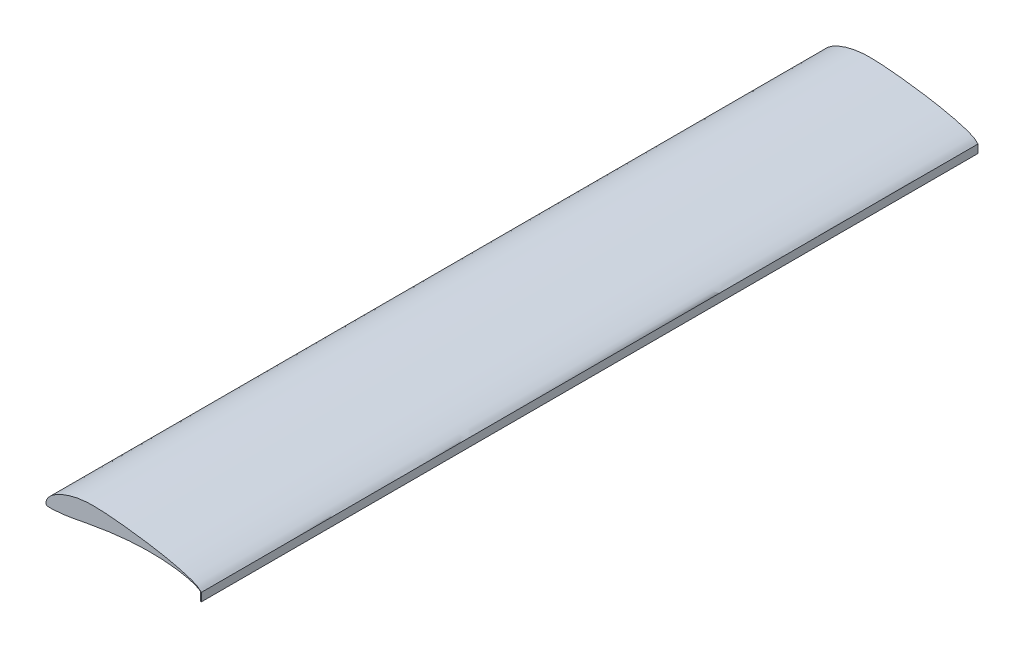
SolidWorks part; units mm, degrees
ref_plane "Front Plane" through (0, 0, 0) normal (0, 0, 1) x (1, 0, 0)
ref_plane "Top Plane" through (0, 0, 0) normal (0, 1, 0) x (1, 0, 0)
ref_plane "Right Plane" through (0, 0, 0) normal (1, 0, 0) x (0, 0, -1)
curve "Curve1"
  spline degree 3 poles (189.7628, 0.4947, 0) (190.6727, -0.123, 0) (189.8749, 0.4714, 0) (189.3453, 0.9911, 0) (188.1693, 2.0765, 0) (186.7819, 3.2312, 0) (184.8841, 4.3952, 0) (182.5241, 5.5233, 0) (179.675, 6.7006, 0) (176.3413, 7.9107, 0) (172.5383, 9.145, 0) (168.286, 10.3929, 0) (163.608, 11.6486, 0) (158.5302, 12.9003, 0) (153.0818, 14.1392, 0) (147.2951, 15.3574, 0) (141.2056, 16.5488, 0) (134.8488, 17.6986, 0) (128.2647, 18.8051, 0) (121.4914, 19.8543, 0) (114.5726, 20.848, 0) (107.5526, 21.7785, 0) (100.4822, 22.6427, 0) (93.4181, 23.4467, 0) (86.4187, 24.1704, 0) (79.541, 24.8, 0) (72.8334, 25.3003, 0) (66.3342, 25.6444, 0) (60.0796, 25.793, 0) (54.1015, 25.7772, 0) (48.4112, 25.4845, 0) (43.0065, 24.8913, 0) (37.8653, 24.0526, 0) (32.9864, 22.9661, 0) (28.3748, 21.6919, 0) (24.0501, 20.2528, 0) (20.0306, 18.6822, 0) (16.3413, 16.9888, 0) (12.994, 15.2068, 0) (10.0069, 13.3564, 0) (7.3989, 11.4629, 0) (5.1709, 9.5662, 0) (3.3552, 7.6458, 0) (1.9605, 5.7182, 0) (0.9303, 3.8429, 0) (0.2701, 2.0624, 0) (-0.0445, 0.419, 0) (0.0162, -0.9709, 0) (0.3741, -2.2457, 0) (1.7042, -2.8785, 0) (3.4926, -2.9673, 0) (5.9392, -3.0533, 0) (9.0159, -2.9207, 0) (12.688, -2.6769, 0) (16.9146, -2.2863, 0) (21.6525, -1.7579, 0) (26.8785, -1.0803, 0) (32.5902, -0.1332, 0) (38.8153, 1.0544, 0) (45.5849, 2.347, 0) (52.8659, 3.7117, 0) (60.6127, 5.092, 0) (68.7684, 6.436, 0) (77.2695, 7.6989, 0) (86.043, 8.8343, 0) (95.0099, 9.8092, 0) (104.0854, 10.5799, 0) (113.1786, 11.1261, 0) (122.1944, 11.4265, 0) (131.035, 11.4644, 0) (139.6018, 11.2374, 0) (147.7967, 10.7507, 0) (155.5211, 10.0106, 0) (162.6831, 9.0456, 0) (169.1894, 7.8836, 0) (174.9638, 6.5636, 0) (179.8998, 5.1511, 0) (183.9394, 3.6435, 0) (186.8216, 2.264, 0) (188.9465, 0.9883, 0) (189.7628, 0.4947, 0) (190.6727, -0.123, 0) (189.8749, 0.4714, 0) knots -0.009748 -0.004147 -0.001 0 0.00098 0.003649 0.007483 0.012095 0.017526 0.024052 0.031783 0.040678 0.05071 0.061833 0.073989 0.087118 0.101145 0.115991 0.13157 0.147788 0.164551 0.181758 0.199312 0.217095 0.23499 0.252857 0.270541 0.287887 0.304773 0.321101 0.336806 0.3518 0.366031 0.379616 0.392653 0.40517 0.417172 0.428604 0.439419 0.449597 0.459102 0.467908 0.475988 0.483309 0.489875 0.495803 0.501149 0.505903 0.510047 0.513579 0.516447 0.51935 0.523823 0.529974 0.537716 0.546968 0.557637 0.56962 0.582804 0.597247 0.613135 0.630444 0.649056 0.668822 0.689595 0.71119 0.733427 0.756094 0.778989 0.80189 0.824567 0.846792 0.868338 0.888978 0.908492 0.926659 0.943286 0.958169 0.971136 0.981956 0.990252 0.995853 0.999 1 1.00098 1.003649 1.007483 periodic
sketch "Sketch1" plane through (0, 0, 0) normal (0, 0, 1) x (1, 0, 0)
  spline S0 degree 3 poles (189.7628, 0.4947) (190.6727, -0.123) (189.8749, 0.4714) (189.3453, 0.9911) (188.1693, 2.0765) (186.7819, 3.2312) (184.8841, 4.3952) (182.5241, 5.5233) (179.675, 6.7006) (176.3413, 7.9107) (172.5383, 9.145) (168.286, 10.3929) (163.608, 11.6486) (158.5302, 12.9003) (153.0818, 14.1392) (147.2951, 15.3574) (141.2056, 16.5488) (134.8488, 17.6986) (128.2647, 18.8051) (121.4914, 19.8543) (114.5726, 20.848) (107.5526, 21.7785) (100.4822, 22.6427) (93.4181, 23.4467) (86.4187, 24.1704) (79.541, 24.8) (72.8334, 25.3003) (66.3342, 25.6444) (60.0796, 25.793) (54.1015, 25.7772) (48.4112, 25.4845) (43.0065, 24.8913) (37.8653, 24.0526) (32.9864, 22.9661) (28.3748, 21.6919) (24.0501, 20.2528) (20.0306, 18.6822) (16.3413, 16.9888) (12.994, 15.2068) (10.0069, 13.3564) (7.3989, 11.4629) (5.1709, 9.5662) (3.3552, 7.6458) (1.9605, 5.7182) (0.9303, 3.8429) (0.2701, 2.0624) (-0.0445, 0.419) (0.0162, -0.9709) (0.3741, -2.2457) (1.7042, -2.8785) (3.4926, -2.9673) (5.9392, -3.0533) (9.0159, -2.9207) (12.688, -2.6769) (16.9146, -2.2863) (21.6525, -1.7579) (26.8785, -1.0803) (32.5902, -0.1332) (38.8153, 1.0544) (45.5849, 2.347) (52.8659, 3.7117) (60.6127, 5.092) (68.7684, 6.436) (77.2695, 7.6989) (86.043, 8.8343) (95.0099, 9.8092) (104.0854, 10.5799) (113.1786, 11.1261) (122.1944, 11.4265) (131.035, 11.4644) (139.6018, 11.2374) (147.7967, 10.7507) (155.5211, 10.0106) (162.6831, 9.0456) (169.1894, 7.8836) (174.9638, 6.5636) (179.8998, 5.1511) (183.9394, 3.6435) (186.8216, 2.264) (188.9465, 0.9883) (189.7628, 0.4947) (190.6727, -0.123) (189.8749, 0.4714) knots -0.009748 -0.004147 -0.001 0 0.00098 0.003649 0.007483 0.012095 0.017526 0.024052 0.031783 0.040678 0.05071 0.061833 0.073989 0.087118 0.101145 0.115991 0.13157 0.147788 0.164551 0.181758 0.199312 0.217095 0.23499 0.252857 0.270541 0.287887 0.304773 0.321101 0.336806 0.3518 0.366031 0.379616 0.392653 0.40517 0.417172 0.428604 0.439419 0.449597 0.459102 0.467908 0.475988 0.483309 0.489875 0.495803 0.501149 0.505903 0.510047 0.513579 0.516447 0.51935 0.523823 0.529974 0.537716 0.546968 0.557637 0.56962 0.582804 0.597247 0.613135 0.630444 0.649056 0.668822 0.689595 0.71119 0.733427 0.756094 0.778989 0.80189 0.824567 0.846792 0.868338 0.888978 0.908492 0.926659 0.943286 0.958169 0.971136 0.981956 0.990252 0.995853 0.999 1 1.00098 1.003649 1.007483 only from (190.5, 0) to (190.5, 0) construction
  spline S1 degree 3 poles (189.7628, 0.4947) (190.6727, -0.123) (189.8749, 0.4714) (189.3453, 0.9911) (188.1693, 2.0765) (186.7819, 3.2312) (184.8841, 4.3952) (182.5241, 5.5233) (179.675, 6.7006) (176.3413, 7.9107) (172.5383, 9.145) (168.286, 10.3929) (163.608, 11.6486) (158.5302, 12.9003) (153.0818, 14.1392) (147.2951, 15.3574) (141.2056, 16.5488) (134.8488, 17.6986) (128.2647, 18.8051) (121.4914, 19.8543) (114.5726, 20.848) (107.5526, 21.7785) (100.4822, 22.6427) (93.4181, 23.4467) (86.4187, 24.1704) (79.541, 24.8) (72.8334, 25.3003) (66.3342, 25.6444) (60.0796, 25.793) (54.1015, 25.7772) (48.4112, 25.4845) (43.0065, 24.8913) (37.8653, 24.0526) (32.9864, 22.9661) (28.3748, 21.6919) (24.0501, 20.2528) (20.0306, 18.6822) (16.3413, 16.9888) (12.994, 15.2068) (10.0069, 13.3564) (7.3989, 11.4629) (5.1709, 9.5662) (3.3552, 7.6458) (1.9605, 5.7182) (0.9303, 3.8429) (0.2701, 2.0624) (-0.0445, 0.419) (0.0162, -0.9709) (0.3741, -2.2457) (1.7042, -2.8785) (3.4926, -2.9673) (5.9392, -3.0533) (9.0159, -2.9207) (12.688, -2.6769) (16.9146, -2.2863) (21.6525, -1.7579) (26.8785, -1.0803) (32.5902, -0.1332) (38.8153, 1.0544) (45.5849, 2.347) (52.8659, 3.7117) (60.6127, 5.092) (68.7684, 6.436) (77.2695, 7.6989) (86.043, 8.8343) (95.0099, 9.8092) (104.0854, 10.5799) (113.1786, 11.1261) (122.1944, 11.4265) (131.035, 11.4644) (139.6018, 11.2374) (147.7967, 10.7507) (155.5211, 10.0106) (162.6831, 9.0456) (169.1894, 7.8836) (174.9638, 6.5636) (179.8998, 5.1511) (183.9394, 3.6435) (186.8216, 2.264) (188.9465, 0.9883) (189.7628, 0.4947) (190.6727, -0.123) (189.8749, 0.4714) knots -0.009748 -0.004147 -0.001 0 0.00098 0.003649 0.007483 0.012095 0.017526 0.024052 0.031783 0.040678 0.05071 0.061833 0.073989 0.087118 0.101145 0.115991 0.13157 0.147788 0.164551 0.181758 0.199312 0.217095 0.23499 0.252857 0.270541 0.287887 0.304773 0.321101 0.336806 0.3518 0.366031 0.379616 0.392653 0.40517 0.417172 0.428604 0.439419 0.449597 0.459102 0.467908 0.475988 0.483309 0.489875 0.495803 0.501149 0.505903 0.510047 0.513579 0.516447 0.51935 0.523823 0.529974 0.537716 0.546968 0.557637 0.56962 0.582804 0.597247 0.613135 0.630444 0.649056 0.668822 0.689595 0.71119 0.733427 0.756094 0.778989 0.80189 0.824567 0.846792 0.868338 0.888978 0.908492 0.926659 0.943286 0.958169 0.971136 0.981956 0.990252 0.995853 0.999 1 1.00098 1.003649 1.007483 only from (190.5, 0) to (190.5, 0)
extrude "Boss-Extrude1" add sketch "Sketch1" along normal blind 952.5
sketch "Sketch2" plane through (0, 0, 0) normal (0, 0, -1) x (-1, 0, 0)
  line L0 (0, 0) -> (-190.5, 0) construction
  line L1 (-190.5, 0) -> (-190.5, -25.3291) construction
  line L2 (0, 0) -> (0, -25.3291) construction
  spline S0 degree 3 poles (-189.8749, 0.4714) (-190.6727, -0.123) (-189.7628, 0.4947) (-188.9465, 0.9883) (-186.8216, 2.264) (-183.9394, 3.6435) (-179.8998, 5.1511) (-174.9638, 6.5636) (-169.1894, 7.8836) (-162.6831, 9.0456) (-155.5211, 10.0106) (-147.7967, 10.7507) (-139.6018, 11.2374) (-131.035, 11.4644) (-122.1944, 11.4265) (-113.1786, 11.1261) (-104.0854, 10.5799) (-95.0099, 9.8092) (-86.043, 8.8343) (-77.2695, 7.6989) (-68.7684, 6.436) (-60.6127, 5.092) (-52.8659, 3.7117) (-45.5849, 2.347) (-38.8153, 1.0544) (-32.5902, -0.1332) (-26.8785, -1.0803) (-21.6525, -1.7579) (-16.9146, -2.2863) (-12.688, -2.6769) (-9.0159, -2.9207) (-5.9392, -3.0533) (-3.4926, -2.9673) (-1.7042, -2.8785) (-0.3741, -2.2457) (-0.0162, -0.9709) (0.0445, 0.419) (-0.2701, 2.0624) (-0.9303, 3.8429) (-1.9605, 5.7182) (-3.3552, 7.6458) (-5.1709, 9.5662) (-7.3989, 11.4629) (-10.0069, 13.3564) (-12.994, 15.2068) (-16.3413, 16.9888) (-20.0306, 18.6822) (-24.0501, 20.2528) (-28.3748, 21.6919) (-32.9864, 22.9661) (-37.8653, 24.0526) (-43.0065, 24.8913) (-48.4112, 25.4845) (-54.1015, 25.7772) (-60.0796, 25.793) (-66.3342, 25.6444) (-72.8334, 25.3003) (-79.541, 24.8) (-86.4187, 24.1704) (-93.4181, 23.4467) (-100.4822, 22.6427) (-107.5526, 21.7785) (-114.5726, 20.848) (-121.4914, 19.8543) (-128.2647, 18.8051) (-134.8488, 17.6986) (-141.2056, 16.5488) (-147.2951, 15.3574) (-153.0818, 14.1392) (-158.5302, 12.9003) (-163.608, 11.6486) (-168.286, 10.3929) (-172.5383, 9.145) (-176.3413, 7.9107) (-179.675, 6.7006) (-182.5241, 5.5233) (-184.8841, 4.3952) (-186.7819, 3.2312) (-188.1693, 2.0765) (-189.3453, 0.9911) (-189.8749, 0.4714) (-190.6727, -0.123) (-189.7628, 0.4947) knots -0.007483 -0.003649 -0.00098 0 0.001 0.004147 0.009748 0.018044 0.028864 0.041831 0.056714 0.073341 0.091508 0.111022 0.131662 0.153208 0.175433 0.19811 0.221011 0.243906 0.266573 0.28881 0.310405 0.331178 0.350944 0.369556 0.386865 0.402753 0.417196 0.43038 0.442363 0.453032 0.462284 0.470026 0.476177 0.48065 0.483553 0.486421 0.489953 0.494097 0.498851 0.504197 0.510125 0.516691 0.524012 0.532092 0.540898 0.550403 0.560581 0.571396 0.582828 0.59483 0.607347 0.620384 0.633969 0.6482 0.663194 0.678899 0.695227 0.712113 0.729459 0.747143 0.76501 0.782905 0.800688 0.818242 0.835449 0.852212 0.86843 0.884009 0.898855 0.912882 0.926011 0.938167 0.94929 0.959322 0.968217 0.975948 0.982474 0.987905 0.992517 0.996351 0.99902 1 1.001 1.004147 1.009748 only from (-190.5, 0) to (-190.5, 0) construction
  spline S1 degree 3 poles (-189.8749, 0.4714) (-190.6727, -0.123) (-189.7628, 0.4947) (-188.9465, 0.9883) (-186.8216, 2.264) (-183.9394, 3.6435) (-179.8998, 5.1511) (-174.9638, 6.5636) (-169.1894, 7.8836) (-162.6831, 9.0456) (-155.5211, 10.0106) (-147.7967, 10.7507) (-139.6018, 11.2374) (-131.035, 11.4644) (-122.1944, 11.4265) (-113.1786, 11.1261) (-104.0854, 10.5799) (-95.0099, 9.8092) (-86.043, 8.8343) (-77.2695, 7.6989) (-68.7684, 6.436) (-60.6127, 5.092) (-52.8659, 3.7117) (-45.5849, 2.347) (-38.8153, 1.0544) (-32.5902, -0.1332) (-26.8785, -1.0803) (-21.6525, -1.7579) (-16.9146, -2.2863) (-12.688, -2.6769) (-9.0159, -2.9207) (-5.9392, -3.0533) (-3.4926, -2.9673) (-1.7042, -2.8785) (-0.3741, -2.2457) (-0.0162, -0.9709) (0.0445, 0.419) (-0.2701, 2.0624) (-0.9303, 3.8429) (-1.9605, 5.7182) (-3.3552, 7.6458) (-5.1709, 9.5662) (-7.3989, 11.4629) (-10.0069, 13.3564) (-12.994, 15.2068) (-16.3413, 16.9888) (-20.0306, 18.6822) (-24.0501, 20.2528) (-28.3748, 21.6919) (-32.9864, 22.9661) (-37.8653, 24.0526) (-43.0065, 24.8913) (-48.4112, 25.4845) (-54.1015, 25.7772) (-60.0796, 25.793) (-66.3342, 25.6444) (-72.8334, 25.3003) (-79.541, 24.8) (-86.4187, 24.1704) (-93.4181, 23.4467) (-100.4822, 22.6427) (-107.5526, 21.7785) (-114.5726, 20.848) (-121.4914, 19.8543) (-128.2647, 18.8051) (-134.8488, 17.6986) (-141.2056, 16.5488) (-147.2951, 15.3574) (-153.0818, 14.1392) (-158.5302, 12.9003) (-163.608, 11.6486) (-168.286, 10.3929) (-172.5383, 9.145) (-176.3413, 7.9107) (-179.675, 6.7006) (-182.5241, 5.5233) (-184.8841, 4.3952) (-186.7819, 3.2312) (-188.1693, 2.0765) (-189.3453, 0.9911) (-189.8749, 0.4714) (-190.6727, -0.123) (-189.7628, 0.4947) knots -0.007483 -0.003649 -0.00098 0 0.001 0.004147 0.009748 0.018044 0.028864 0.041831 0.056714 0.073341 0.091508 0.111022 0.131662 0.153208 0.175433 0.19811 0.221011 0.243906 0.266573 0.28881 0.310405 0.331178 0.350944 0.369556 0.386865 0.402753 0.417196 0.43038 0.442363 0.453032 0.462284 0.470026 0.476177 0.48065 0.483553 0.486421 0.489953 0.494097 0.498851 0.504197 0.510125 0.516691 0.524012 0.532092 0.540898 0.550403 0.560581 0.571396 0.582828 0.59483 0.607347 0.620384 0.633969 0.6482 0.663194 0.678899 0.695227 0.712113 0.729459 0.747143 0.76501 0.782905 0.800688 0.818242 0.835449 0.852212 0.86843 0.884009 0.898855 0.912882 0.926011 0.938167 0.94929 0.959322 0.968217 0.975948 0.982474 0.987905 0.992517 0.996351 0.99902 1 1.001 1.004147 1.009748 only from (-190.5, 0) to (-190.5, 0) construction
sketch "Sketch3" plane through (0, 0, 952.5) normal (0, 0, 1) x (1, 0, 0)
  line L0 (0, 0) -> (0, -25.3291) construction
  line L1 (0, 0) -> (190.5, 0) construction
  line L2 (190.5, 0) -> (190.5, -25.3291) construction
  line L3 (0, 0) -> (0, -25.3291) construction
  line L4 (0, 0) -> (190.5, 0) construction
  line L5 (190.5, 0) -> (190.5, -25.3291) construction
sketch "Sketch4" plane through (0, 0, 952.5) normal (0, 0, 1) x (1, 0, 0)
  line L0 (190.5, 0) -> (190.5, -10.16)
  line L1 (190.5, 0) -> (190.5, -25.3291) construction
  line L2 (190.5, -10.16) -> (189.23, -10.16)
  line L3 (189.23, -10.16) -> (189.23, 0.9487)
  line L4 (189.23, 0.9487) -> (190.5, 0)
  dimension "D1" = 10.16
  dimension "D2" = 1.27
extrude "Boss-Extrude2" add sketch "Sketch4" against normal through all
sketch3d "3DSketch1"
  line L0 (0, 0, 952.5) -> (0, 0, 0) construction
ref_plane "Plane1" through (0, 0, 476.25) normal (0, 0, -1) x (-1, 0, 0)
